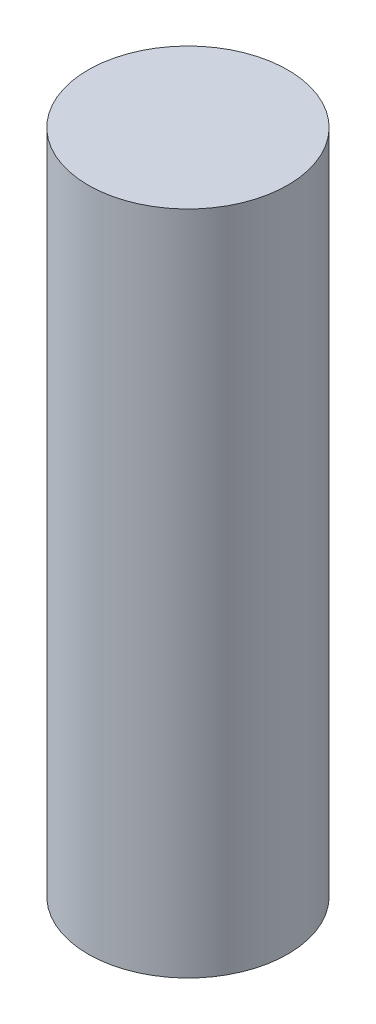
SolidWorks part; units mm, degrees
ref_plane "Ön Düzlem" through (0, 0, 0) normal (0, 0, 1) x (1, 0, 0)
ref_plane "Üst Düzlem" through (0, 0, 0) normal (0, 1, 0) x (1, 0, 0)
ref_plane "Sağ Düzlem" through (0, 0, 0) normal (1, 0, 0) x (0, 0, -1)
sketch "Çizim1" plane through (0, 0, 0) normal (0, 1, 0) x (1, 0, 0)
  circle A0 centre (0, 0) radius 7.495
  dimension "D1" = 14.99
extrude "Yükseklik-Ekstrüzyon1" add sketch "Çizim1" along normal blind 50
